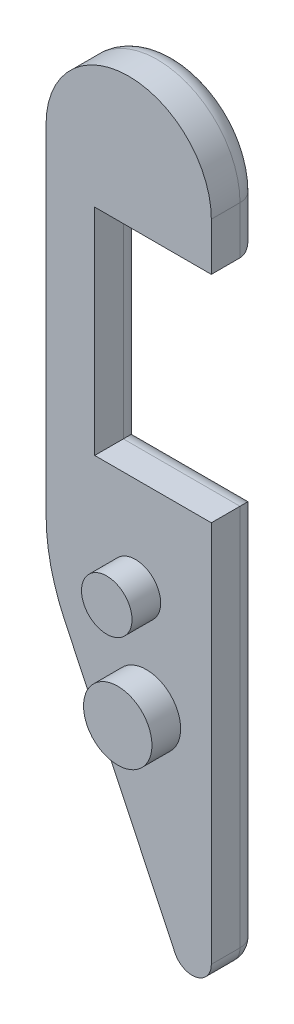
SolidWorks part; units mm, degrees
ref_plane "前基準面" through (0, 0, 0) normal (0, 0, 1) x (1, 0, 0)
ref_plane "上基準面" through (0, 0, 0) normal (0, 1, 0) x (1, 0, 0)
ref_plane "右基準面" through (0, 0, 0) normal (1, 0, 0) x (0, 0, -1)
sketch "草圖1" plane through (0, 0, 0) normal (0, 0, 1) x (1, 0, 0)
  line L0 (0, 0) -> (-12.2, 0)
  line L1 (-12.2, 0) -> (-12.2, -22.5)
  line L2 (-12.2, -22.5) -> (0, -22.5)
  line L3 (0, -22.5) -> (0, -62.5)
  line L4 (-3.8075, -63.3562) -> (-15.359, -38.971)
  line L5 (-17.2844, -30.4089) -> (-17.2844, 5)
  line L6 (0, 5) -> (0, 0)
  arc A0 (-17.2844, 5) -> (0, 5) centre (-8.6422, 5) cw
  arc A1 (0, -62.5) -> (-3.8075, -63.3562) centre (-2, -62.5) cw
  arc A2 (-15.359, -38.971) -> (-17.2844, -30.4089) centre (2.7156, -30.4089) cw
  dimension "D2" = 2
  dimension "D5" = 20
  dimension "D1" = 22.5
  dimension "D3" = 40
  dimension "D4" = 5
  dimension "D8" = 12.2
extrude "填料-伸長1" add sketch "草圖1" along normal blind 5
sketch "草圖3" plane through (0, 0, 5) normal (0, 0, 1) x (1, 0, 0)
  circle A0 centre (-7.9389, -32.4258) radius 2.6402
  circle A1 centre (-6.7884, -42.772) radius 3.5783
extrude "填料-伸長2" add sketch "草圖3" along normal blind 3
fillet "圓角3" radius 2 10 edges at (-8.6422, 13.6422, 0) (-17.2844, -12.7044, 0) (-16.7971, -34.7968, 0) (-9.5832, -51.1636, 0) (-1.5612, -64.4513, 0) (0, -42.5, 0) (-6.1, -22.5, 0) (-12.2, -11.25, 0) (-6.1, 0, 0) (0, 2.5, 0)
